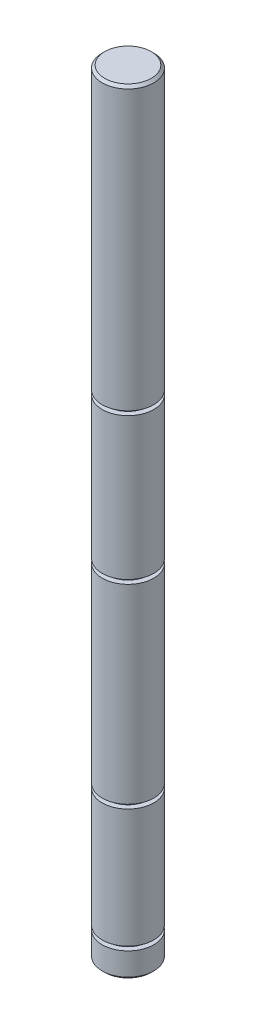
SolidWorks part; units mm, degrees
ref_plane "Front Plane" through (0, 0, 0) normal (0, 0, 1) x (1, 0, 0)
ref_plane "Top Plane" through (0, 0, 0) normal (0, 1, 0) x (1, 0, 0)
ref_plane "Right Plane" through (0, 0, 0) normal (1, 0, 0) x (0, 0, -1)
sketch "Sketch1" plane through (0, 0, 0) normal (0, 1, 0) x (1, 0, 0)
  circle A0 centre (0, 0) radius 5
  dimension "D1" = 10
extrude "Boss-Extrude1" add sketch "Sketch1" along normal blind 150
chamfer "Chamfer1" distance 0.5 angle 45 2 edges at (0, 150, 5) (0, 0, 5)
sketch "Sketch2" plane through (0, 0, 0) normal (0, 0, 1) x (1, 0, 0)
  line L0 (-5, 149.5) -> (-5, 0.5) construction
  line L1 (-5, 67.2) -> (-4, 67.2)
  line L2 (-5, 67.2) -> (-5, 66.4)
  line L3 (-5, 66.4) -> (-4, 66.4)
  line L4 (-4, 67.2) -> (-4, 66.4)
  line L6 (0, 141.9078) -> (0, 108.4288) construction
  dimension "D1" = 1
  dimension "D2" = 0.8
  dimension "D3" = 67.2
revolve "Cut-Revolve1" cut sketch "Sketch2" angle 360 about L6
pattern_linear "LPattern1" count 2 spacing 28.3 along (0, 1, 0) of "Cut-Revolve1"
sketch "Sketch3" plane through (0, 0, 0) normal (0, 0, 1) x (1, 0, 0)
  line L0 (-5, 149.5) -> (-5, 95.5) construction
  line L1 (-5, 5.7) -> (-4, 5.7)
  line L2 (-5, 5.7) -> (-5, 4.9)
  line L3 (-5, 4.9) -> (-4, 4.9)
  line L4 (-4, 5.7) -> (-4, 4.9)
  line L6 (-4, 29.5) -> (-4, 28.7)
  line L7 (-5, 29.5) -> (-4, 29.5)
  line L8 (-5, 29.5) -> (-5, 28.7)
  line L9 (-5, 28.7) -> (-4, 28.7)
  line L10 (0, 152.9046) -> (0, 137.2168) construction
  line L11 (-4.5, 0) -> (4.5, 0) construction
  dimension "D1" = 1
  dimension "D2" = 0.8
  dimension "D3" = 5.7
  dimension "D5" = 28.7
  dimension "D4" = 2
revolve "Cut-Revolve2" cut sketch "Sketch3" angle 360 about L10
